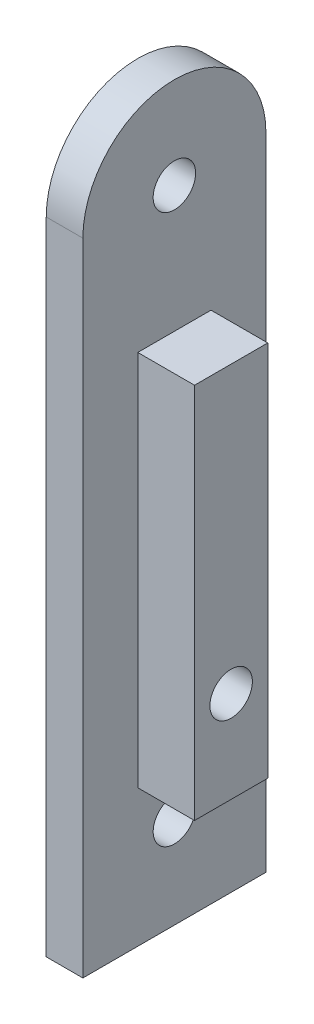
SolidWorks part; units mm, degrees
ref_plane "Front Plane" through (0, 0, 0) normal (0, 0, 1) x (1, 0, 0)
ref_plane "Top Plane" through (0, 0, 0) normal (0, 1, 0) x (1, 0, 0)
ref_plane "Right Plane" through (0, 0, 0) normal (1, 0, 0) x (0, 0, -1)
sketch "Sketch1" plane through (0, 0, 0) normal (1, 0, 0) x (0, 0, -1)
  line L4 (6.35, -44.45) -> (6.35, 0)
  line L5 (-6.35, 0) -> (-6.35, -44.45)
  line L6 (6.35, -44.45) -> (-6.35, -44.45)
  arc A2 (6.35, 0) -> (-6.35, 0) centre (0, 0) ccw
  dimension "D1" = 6.35
  dimension "D2" = 44.45
extrude "Boss-Extrude1" add sketch "Sketch1" along normal blind 2.54
sketch "Sketch2" plane through (2.54, 0, 0) normal (1, 0, 0) x (0, 0, -1)
  line L0 (-2.54, -34.925) -> (-2.54, -8.7723)
  line L1 (-2.54, -8.7723) -> (2.54, -8.7723)
  line L2 (2.54, -8.7723) -> (2.54, -34.925)
  line L3 (2.54, -34.925) -> (-2.54, -34.925)
  line L4 (-2.54, -21.8486) -> (-6.35, -21.8486) construction
  line L5 (-6.35, 0) -> (-6.35, -44.45) construction
  line L6 (2.54, -21.8486) -> (6.35, -21.8486) construction
  line L7 (6.35, -44.45) -> (6.35, 0) construction
  line L8 (0, -8.7723) -> (0, 0) construction
  line L10 (0, -34.925) -> (0, -44.45) construction
  line L11 (-6.35, -44.45) -> (6.35, -44.45) construction
  dimension "D1" = 9.525
  dimension "D2" = 3.81
  dimension "D3" = 8.7723
extrude "Boss-Extrude2" add sketch "Sketch2" along normal blind 3.937
sketch "Sketch3" plane through (0, 0, 0) normal (-1, 0, 0) x (0, 0, 1)
  circle A2 centre (0, 0) radius 1.4732
  dimension "D1" = 2.9464
extrude "Cut-Extrude1" cut sketch "Sketch3" against normal through all both and the other way through all
sketch "Sketch4" plane through (0, 0, 0) normal (-1, 0, 0) x (0, 0, 1)
  line L0 (0, 0) -> (0, -28.575)
  line L1 (0, -28.575) -> (0, -38.1)
  dimension "D1" = 28.575
  dimension "D2" = 9.525
hole_wizard "#4 Clearance Hole1" positions "Sketch5" profile "Sketch6" hole size "#4" standard "ANSI Inch" end condition through all
sketch "Sketch5" plane through (0, 0, 0) normal (-1, 0, 0) x (0, 0, 1)
  point P0 (0, -28.575)
  point P3 (0, -38.1)
sketch "Sketch6" plane through (0, -28.575, 0) normal (0, 1, 0) x (0, 0, 1)
  line L0 (0, 0) -> (0, 6.477)
  line L1 (0, 6.477) -> (1.4732, 6.477)
  line L2 (1.4732, 6.477) -> (1.4732, 0)
  line L5 (1.4732, 0) -> (0, 0)
  line L11 (0, -6.35) -> (0, 107.95) construction
  dimension "Thru Hole Dia." = 2.9464
  dimension "Thru Hole Depth" = 6.477
